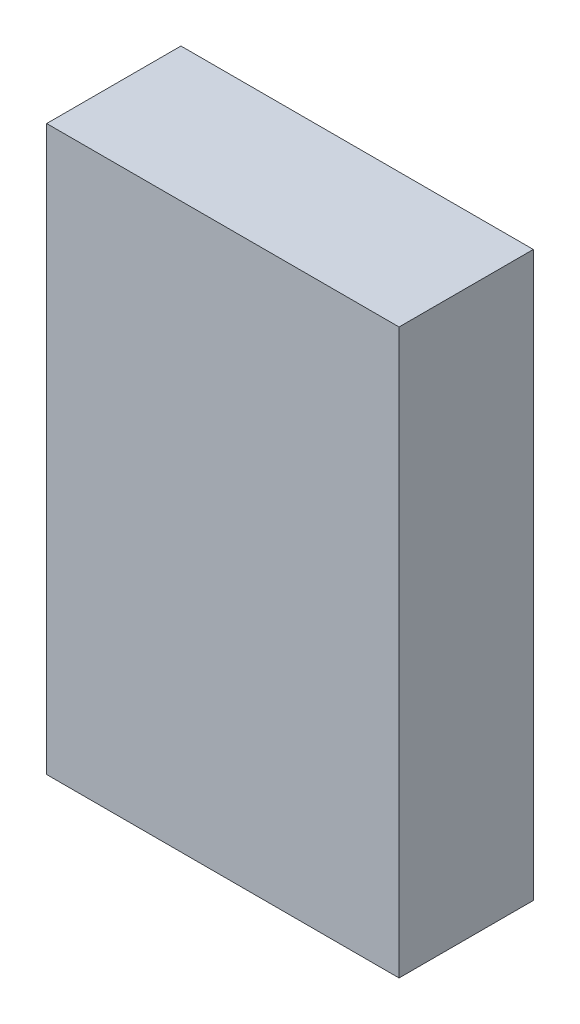
SolidWorks part; units mm, degrees
material "POLYURETHANE (11671)"
ref_plane "Front Plane" through (0, 0, 0) normal (0, 0, 1) x (1, 0, 0)
ref_plane "Top Plane" through (0, 0, 0) normal (0, 1, 0) x (1, 0, 0)
ref_plane "Right Plane" through (0, 0, 0) normal (1, 0, 0) x (0, 0, -1)
sketch "Sketch1" plane through (0, 0, 0) normal (0, 0, 1) x (1, 0, 0)
  line L1 (-12.5, 20) -> (12.5, 20)
  line L2 (-12.5, 20) -> (-12.5, -20)
  line L3 (-12.5, -20) -> (12.5, -20)
  line L4 (12.5, 20) -> (12.5, -20)
  line L5 (-12.5, 20) -> (12.5, -20) construction
  line L6 (-12.5, -20) -> (12.5, 20) construction
  point P0 (0, 0)
  dimension "D1" = 25
  dimension "LENGTH" = 40
extrude "Boss-Extrude1" add sketch "Sketch1" along normal blind 9.525
